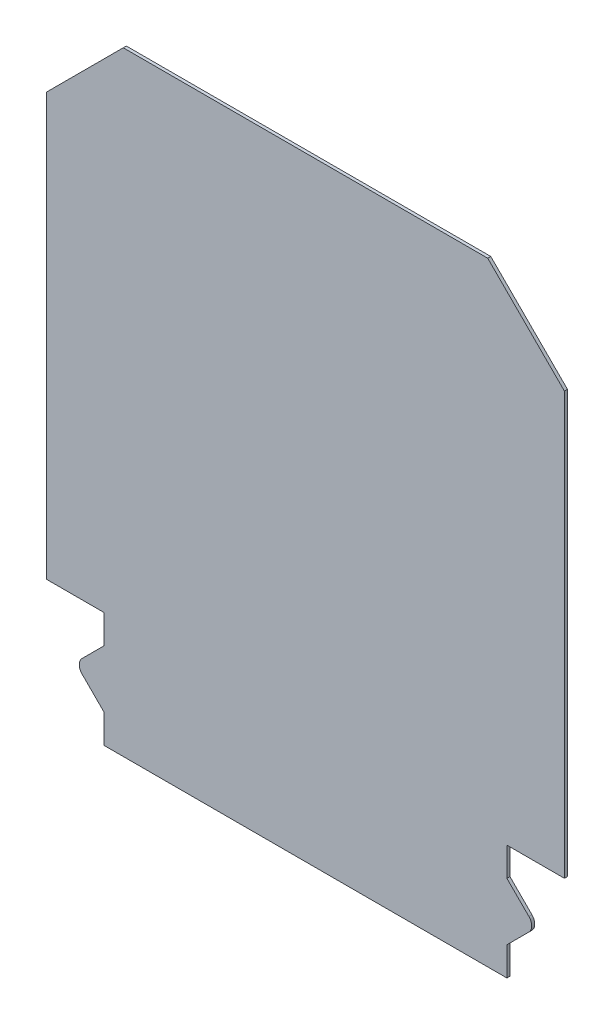
SolidWorks part; units mm, degrees
ref_plane "Front Plane" through (0, 0, 0) normal (0, 0, 1) x (1, 0, 0)
ref_plane "Top Plane" through (0, 0, 0) normal (0, 1, 0) x (1, 0, 0)
ref_plane "Right Plane" through (0, 0, 0) normal (1, 0, 0) x (0, 0, -1)
sketch "Sketch2" plane through (0, 0, 0) normal (0, 0, 1) x (1, 0, 0)
  line L1 (0, 0) -> (540, 0)
  line L2 (0, 0) -> (0, 640)
  line L3 (0, 640) -> (540, 640)
  line L4 (540, 0) -> (540, 640)
  dimension "D1" = 640
  dimension "D2" = 540
extrude "Boss-Extrude1" add sketch "Sketch2" along normal blind 3.175
sketch "Sketch3" plane through (0, 0, 3.175) normal (0, 0, 1) x (1, 0, 0)
  line L0 (0, 640) -> (0, 560)
  line L1 (0, 640) -> (0, 0) construction
  line L2 (0, 560) -> (80, 640)
  line L3 (540, 640) -> (0, 640) construction
  line L4 (80, 640) -> (0, 640)
  line L5 (0, 0) -> (540, 0) construction
  line L6 (270, 0) -> (270, 640) construction
  line L7 (540, 560) -> (460, 640)
  line L8 (460, 640) -> (540, 640)
  line L9 (540, 640) -> (540, 560)
  line L10 (0, 120) -> (60, 120)
  line L11 (60, 120) -> (60, 90)
  line L12 (60, 90) -> (30, 60)
  line L13 (30, 60) -> (60, 30)
  line L14 (60, 30) -> (60, 0)
  line L15 (60, 0) -> (0, 0)
  line L16 (0, 0) -> (0, 120)
  line L17 (540, 0) -> (540, 120)
  line L18 (480, 0) -> (540, 0)
  line L19 (480, 30) -> (480, 0)
  line L20 (510, 60) -> (480, 30)
  line L21 (480, 90) -> (510, 60)
  line L22 (480, 120) -> (480, 90)
  line L23 (540, 120) -> (480, 120)
  dimension "D1" = 80
  dimension "D2" = 120
  dimension "D3" = 30
  dimension "D4" = 60
extrude "Cut-Extrude1" cut sketch "Sketch3" against normal through all
fillet "Fillet1" radius 10 2 edges at (510, 60, 1.5875) (30, 60, 1.5875)
